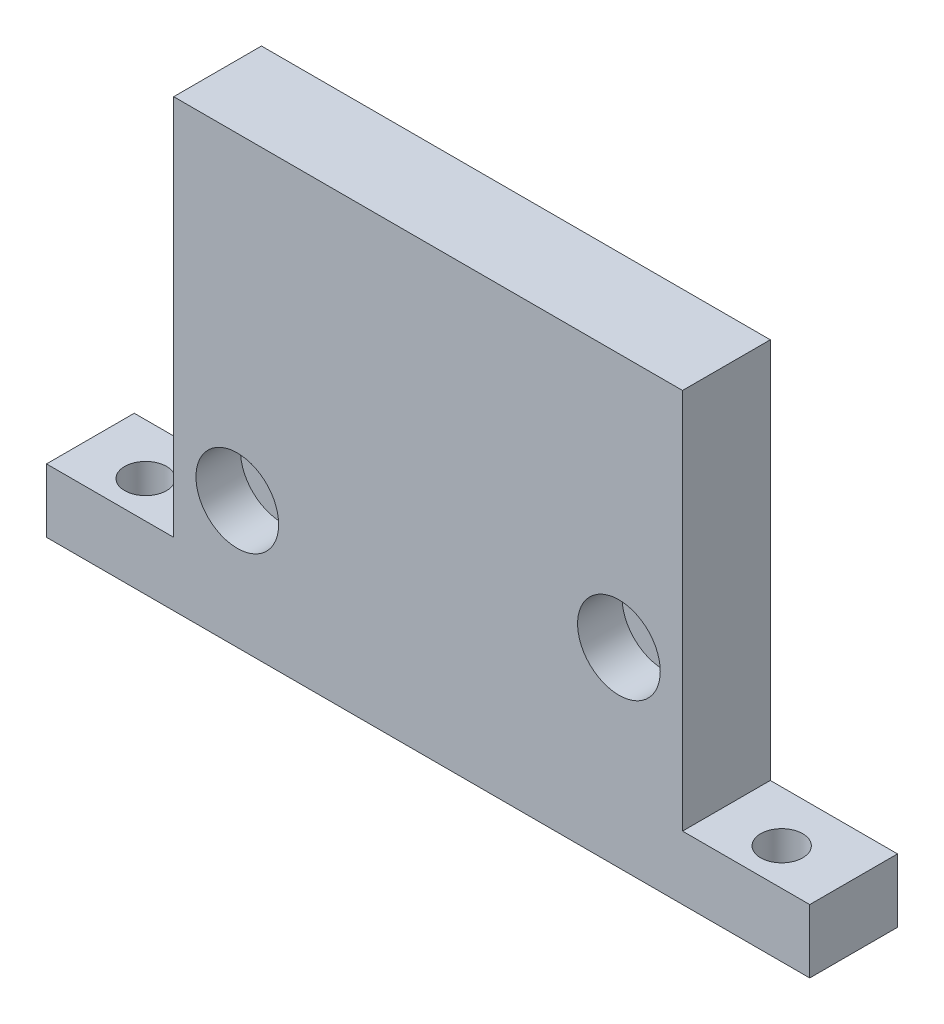
SolidWorks part; units mm, degrees
ref_plane "前视基准面" through (0, 0, 0) normal (0, 0, 1) x (1, 0, 0)
ref_plane "上视基准面" through (0, 0, 0) normal (0, 1, 0) x (1, 0, 0)
ref_plane "右视基准面" through (0, 0, 0) normal (1, 0, 0) x (0, 0, -1)
other "Configuration Table"
sketch "草图1" plane through (0, 0, 0) normal (0, 1, 0) x (1, 0, 0)
  line L1 (-42.9709, 4.5279) -> (17.0291, 4.5279)
  line L2 (-42.9709, 4.5279) -> (-42.9709, -2.3721)
  line L3 (-42.9709, -2.3721) -> (17.0291, -2.3721)
  line L4 (17.0291, 4.5279) -> (17.0291, -2.3721)
  dimension "D1" = 6.9
  dimension "D2" = 60
extrude "凸台-拉伸1" add sketch "草图1" along normal blind 5
sketch "草图2" plane through (0, 0, 0) normal (0, -1, 0) x (1, 0, 0)
  circle A0 centre (11.9231, -0.5279) radius 1.65
  circle A1 centre (-38.0769, -0.5279) radius 1.65
extrude "切除-拉伸1" cut sketch "草图2" against normal blind 10
sketch "草图3" plane through (0, 5, 0) normal (0, 1, 0) x (1, 0, 0)
  line L1 (7.0291, 4.5279) -> (-32.9709, 4.5279)
  line L2 (7.0291, 4.5279) -> (7.0291, -2.3721)
  line L3 (7.0291, -2.3721) -> (-32.9709, -2.3721)
  line L4 (-42.9709, 4.5279) -> (-42.9709, -2.3721)
  line L5 (-42.9709, -2.3721) -> (17.0291, -2.3721)
  line L6 (17.0291, -2.3721) -> (17.0291, 4.5279)
  line L7 (17.0291, 4.5279) -> (-42.9709, 4.5279)
  line L8 (-42.9709, 4.5279) -> (-42.9709, -2.3721)
  line L9 (-42.9709, -2.3721) -> (17.0291, -2.3721)
  line L10 (17.0291, -2.3721) -> (17.0291, 4.5279)
  line L11 (17.0291, 4.5279) -> (-42.9709, 4.5279)
  line L12 (-32.9709, 4.5279) -> (-32.9709, -2.3721)
  point P8 (-12.9709, 4.5279)
  point P9 (-12.9709, 4.5279)
  line M12 (-42.9709, -2.3721) -> (17.0291, -2.3721)
  line M14 (17.0291, 4.5279) -> (-42.9709, 4.5279)
  dimension "D2" = 40
  dimension "D1" = 0
extrude "凸台-拉伸2" add sketch "草图3" along normal blind 30 contours L12 L2 M14 M12
sketch "草图5" plane through (0, 0, -4.5279) normal (0, 0, -1) x (-1, 0, 0)
  line L0 (12.9709, 0) -> (12.9709, 35) construction
  line L2 (27.9709, 10) -> (-2.0291, 10)
  line L3 (27.9709, 10) -> (27.9709, 15)
  line L4 (27.9709, 15) -> (-2.0291, 15)
  line L5 (-2.0291, 10) -> (-2.0291, 15)
  line L6 (27.9709, 10) -> (-2.0291, 15) construction
  line L7 (27.9709, 15) -> (-2.0291, 10) construction
  line L8 (-17.0291, 0) -> (42.9709, 0)
  line L9 (42.9709, 0) -> (42.9709, 5)
  line L10 (42.9709, 5) -> (32.9709, 5)
  line L11 (32.9709, 5) -> (32.9709, 35)
  line L12 (32.9709, 35) -> (-7.0291, 35)
  line L13 (-7.0291, 35) -> (-7.0291, 5)
  line L14 (-7.0291, 5) -> (-17.0291, 5)
  line L15 (-17.0291, 5) -> (-17.0291, 0)
  line L16 (-17.0291, 0) -> (42.9709, 0)
  line L17 (42.9709, 0) -> (42.9709, 5)
  line L18 (42.9709, 5) -> (32.9709, 5)
  line L19 (32.9709, 5) -> (32.9709, 35)
  line L20 (32.9709, 35) -> (-7.0291, 35)
  line L21 (-7.0291, 35) -> (-7.0291, 5)
  line L22 (-7.0291, 5) -> (-17.0291, 5)
  line L23 (-17.0291, 5) -> (-17.0291, 0)
  circle A0 centre (27.9709, 10) radius 1.65
  circle A3 centre (-2.0291, 15) radius 1.65
  point P6 (12.9709, 12.5)
  dimension "D5" = 3.3
  dimension "D2" = 30
  dimension "D3" = 5
  dimension "D4" = 5
  dimension "D1" = 0
extrude "切除-拉伸2" cut sketch "草图5" against normal blind 25 contours A3 | A0
sketch "草图6" plane through (0, 0, 2.3721) normal (0, 0, 1) x (1, 0, 0)
  line L8 (-42.9709, 0) -> (17.0291, 0)
  line L9 (17.0291, 0) -> (17.0291, 5)
  line L10 (17.0291, 5) -> (7.0291, 5)
  line L11 (7.0291, 5) -> (7.0291, 35)
  line L12 (7.0291, 35) -> (-32.9709, 35)
  line L13 (-32.9709, 35) -> (-32.9709, 5)
  line L14 (-32.9709, 5) -> (-42.9709, 5)
  line L15 (-42.9709, 5) -> (-42.9709, 0)
  line L16 (-42.9709, 0) -> (17.0291, 0)
  line L17 (17.0291, 0) -> (17.0291, 5)
  line L18 (17.0291, 5) -> (7.0291, 5)
  line L19 (7.0291, 5) -> (7.0291, 35)
  line L20 (7.0291, 35) -> (-32.9709, 35)
  line L21 (-32.9709, 35) -> (-32.9709, 5)
  line L22 (-32.9709, 5) -> (-42.9709, 5)
  line L23 (-42.9709, 5) -> (-42.9709, 0)
  circle A0 centre (2.0291, 15) radius 1.65 construction
  circle A1 centre (-27.9709, 10) radius 1.65 construction
  circle A2 centre (2.0291, 15) radius 1.65
  circle A3 centre (-27.9709, 10) radius 1.65
  circle A4 centre (-27.9709, 10) radius 3.25
  circle A5 centre (2.0291, 15) radius 3.25
  circle M9 centre (2.0291, 15) radius 1.65
  circle M10 centre (-27.9709, 10) radius 1.65
  dimension "D2" = 6.5
  dimension "D3" = 6.5
  dimension "D1" = 0
extrude "切除-拉伸3" cut sketch "草图6" against normal blind 3.5 contours A4 M10 | A5 M9
